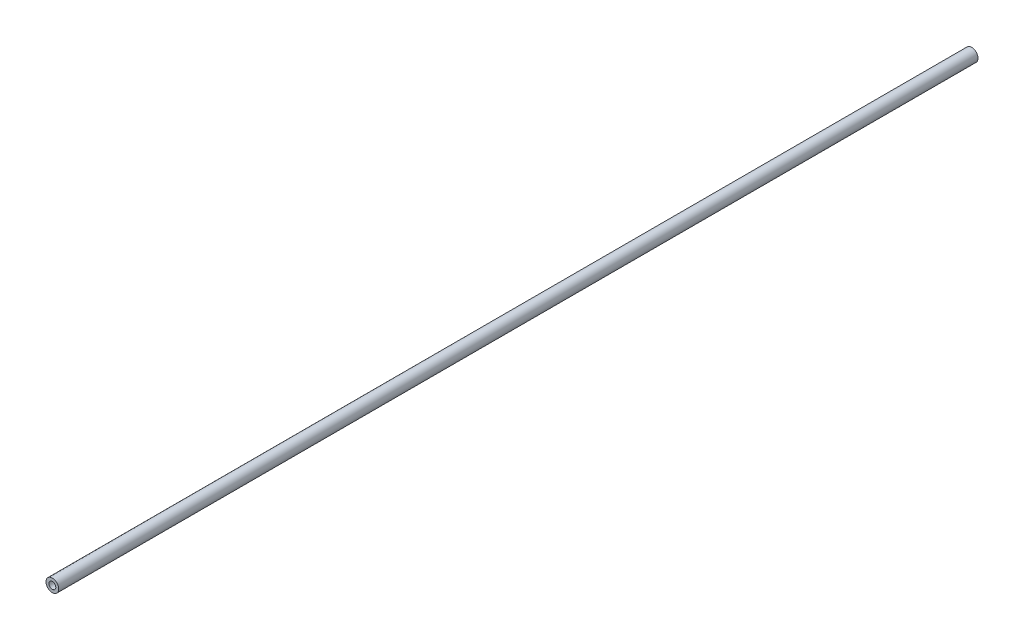
SolidWorks part; units mm, degrees
material "Rubber"
ref_plane "Front Plane" through (0, 0, 0) normal (0, 0, 1) x (1, 0, 0)
ref_plane "Top Plane" through (0, 0, 0) normal (0, 1, 0) x (1, 0, 0)
ref_plane "Right Plane" through (0, 0, 0) normal (1, 0, 0) x (0, 0, -1)
sketch "Sketch1" plane through (0, 0, 0) normal (0, 0, 1) x (1, 0, 0)
  circle A0 centre (0, 0) radius 2.2225
  circle A1 centre (0, 0) radius 1.2065
  dimension "D1" = 4.445
  dimension "D2" = 1.016
extrude "Extrude1" add sketch "Sketch1" along normal blind 322.072
sketch3d "3DSketch1"
  line L0 (0, 0, 322.072) -> (0, 0, 0) construction
  point P0 (0, 0, 322.072)
  point P1 (0, 0, 0)
